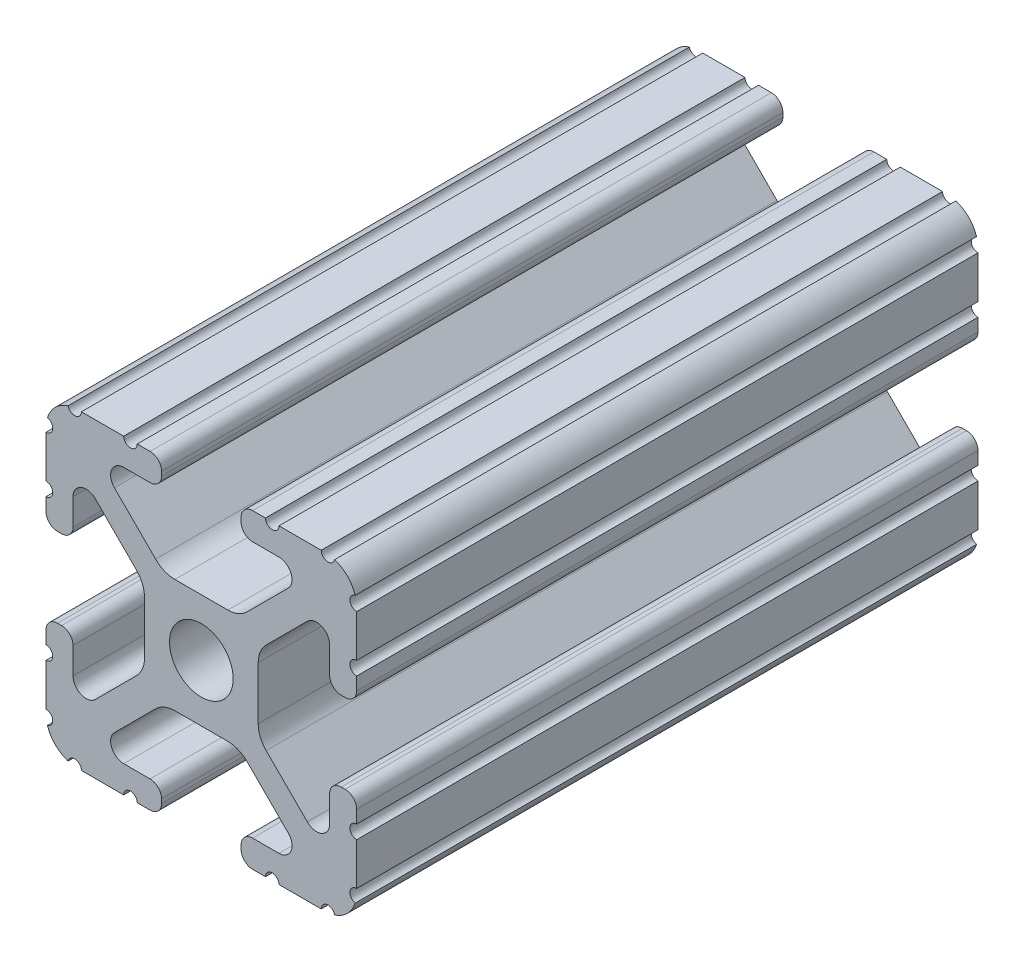
SolidWorks part; units mm, degrees
ref_plane "Front Plane" through (0, 0, 0) normal (0, 0, 1) x (1, 0, 0)
ref_plane "Top Plane" through (0, 0, 0) normal (0, 1, 0) x (1, 0, 0)
ref_plane "Right Plane" through (0, 0, 0) normal (1, 0, 0) x (0, 0, -1)
sketch "Sketch2" plane through (0, 0, 0) normal (0, 0, 1) x (1, 0, 0)
  line L0 (0, 12.7) -> (0, -12.7) construction
  line L1 (-12.7, 0) -> (12.7, 0) construction
  line L2 (3.2512, -12.7) -> (12.7, -12.7)
  line L3 (12.7, -12.7) -> (12.7, -3.2512)
  line L4 (3.2512, -12.7) -> (3.2512, -10.4902)
  line L5 (3.2512, -10.4902) -> (8.9276, -10.4902)
  line L6 (8.9276, -10.4902) -> (3.0856, -4.6482)
  line L7 (0, 0) -> (12.7, -12.7) construction
  line L8 (12.7, -3.2512) -> (10.4902, -3.2512)
  line L9 (10.4902, -3.2512) -> (10.4902, -8.9276)
  line L10 (10.4902, -8.9276) -> (4.6482, -3.0856)
  circle A0 centre (0, 0) radius 2.6035
  arc A1 (6.3485, -10.4902) -> (7.1039, -8.6665) centre (6.3485, -9.4219) ccw construction
  point P8 (0, -4.6482)
  dimension "Center Hole Diameter" = 5.207
  dimension "Rail Height" = 25.4
  dimension "Rail Width" = 25.4
  dimension "T-Slot Width" = 6.5024
  dimension "Slot Inner Width" = 14.8336
  dimension "Thickness" = 2.2098
  dimension "Slot Depth" = 5.842
  dimension "D1" = 2.2098
sketch "Sketch3" plane through (0, 0, 0) normal (1, 0, 0) x (0, 0, -1)
  line L0 (-25.4, -12.7) -> (25.4, -12.7) construction
  line L1 (-22.86, 0) -> (22.86, 0) construction
  dimension "Length" = 50.8
  dimension "D1" = 45.72
sketch "Sketch4" plane through (0, 0, 0) normal (0, 0, 1) x (1, 0, 0)
  line L0 (4.1904, -12.7) -> (10.1173, -12.7)
  line L1 (3.2512, -12.7) -> (12.7, -12.7) construction
  line L2 (3.2512, -12.7) -> (3.2512, -10.4902) construction
  line L3 (3.2512, -10.4902) -> (8.9276, -10.4902) construction
  line L4 (3.2512, -11.4294) -> (3.2512, -11.7608)
  line L5 (4.1904, -10.4902) -> (6.3485, -10.4902)
  line L6 (0, -4.6482) -> (2.164, -4.6482)
  line L7 (8.9276, -10.4902) -> (3.0856, -4.6482) construction
  line L8 (3.7373, -5.2999) -> (7.1039, -8.6665)
  line L9 (12.7, -12.7) -> (12.7, -3.2512) construction
  line L10 (10.4902, -8.9276) -> (4.6482, -3.0856) construction
  line L11 (10.4902, -3.2512) -> (10.4902, -8.9276) construction
  line L12 (10.4902, -6.3485) -> (10.4902, -4.1904)
  line L13 (12.7, -3.2512) -> (10.4902, -3.2512) construction
  line L14 (11.4294, -3.2512) -> (11.7608, -3.2512)
  line L15 (12.7, -4.1904) -> (12.7, -10.1173)
  line L16 (8.6665, -7.1039) -> (5.2999, -3.7373)
  line L17 (4.6482, 0) -> (4.6482, -2.164)
  line L18 (-12.7, 0) -> (12.7, 0) construction
  line L19 (0, -4.6482) -> (0, -2.6035)
  line L20 (0, 12.7) -> (0, -12.7) construction
  line L21 (4.6482, 0) -> (2.6035, 0)
  arc A0 (3.2512, -11.7608) -> (4.1904, -12.7) centre (4.1904, -11.7608) ccw
  arc A2 (3.2512, -11.4294) -> (4.1904, -10.4902) centre (4.1904, -11.4294) cw
  arc A3 (6.3485, -10.4902) -> (7.1039, -8.6665) centre (6.3485, -9.4219) ccw
  arc A4 (2.164, -4.6482) -> (3.7373, -5.2999) centre (2.164, -6.8732) cw
  arc A5 (10.1173, -12.7) -> (12.7, -10.1173) centre (10.1173, -10.1173) ccw
  arc A6 (8.6665, -7.1039) -> (10.4902, -6.3485) centre (9.4219, -6.3485) ccw
  arc A7 (10.4902, -4.1904) -> (11.4294, -3.2512) centre (11.4294, -4.1904) cw
  arc A8 (11.7608, -3.2512) -> (12.7, -4.1904) centre (11.7608, -4.1904) cw
  arc A9 (5.2999, -3.7373) -> (4.6482, -2.164) centre (6.8732, -2.164) cw
  circle A10 centre (0, 0) radius 2.6035 construction
  arc A11 (0, -2.6035) -> (2.6035, 0) centre (0, 0) ccw
  dimension "D1" = 2.5827
  dimension "D2" = 2.225
  dimension "D3" = 0.9392
extrude "Boss-Extrude1" add sketch "Sketch4" along normal mid plane 50.8
sketch "Sketch5" plane through (0, 0, 0) normal (0, 0, 1) x (1, 0, 0)
  line L0 (3.2512, -12.7) -> (12.7, -12.7) construction
  line L1 (4.1904, -10.4902) -> (6.3485, -10.4902) construction
  line L3 (0, 0) -> (12.7, -12.7) construction
  line L4 (6.3485, -10.4902) -> (6.3485, -12.7) construction
  line L5 (8.9276, -10.4902) -> (3.0856, -4.6482) construction
  circle A0 centre (10.3562, -12.7) radius 0.5524
  circle A1 centre (5.796, -12.7) radius 0.5524
  circle A2 centre (12.7, -10.3562) radius 0.5524
  circle A3 centre (12.7, -5.796) radius 0.5524
  point P10 (5.2694, -10.4902)
  point P12 (9.4219, -6.3485)
  dimension "D1" = 1.1049
extrude "Cut-Extrude1" cut sketch "Sketch5" against normal through all both and the other way through all
mirror "Mirror1" about plane through (0, 0, 0) normal (1, 0, 0) of bodies 137 134
mirror "Mirror2" about plane through (0, 0, 0) normal (0, 1, 0) of bodies 135
equation "\"D1@Boss-Extrude1\"=\"Length@Sketch3\""
equation "\"D1@Sketch2\"=\"Thickness@Sketch2\""
equation "\"D2@Sketch4\"=\"Slot Inner Width@Sketch2\"*0.15"
equation "\"D1@Sketch4\"=\"D3@Sketch4\"*2.75"
equation "\"D3@Sketch4\"=\"Thickness@Sketch2\"*0.425"
equation "\"D1@Sketch5\"=\"Thickness@Sketch2\"*0.5"
equation "\"D1@Sketch3\"=\"Length@Sketch3\"*0.9"
